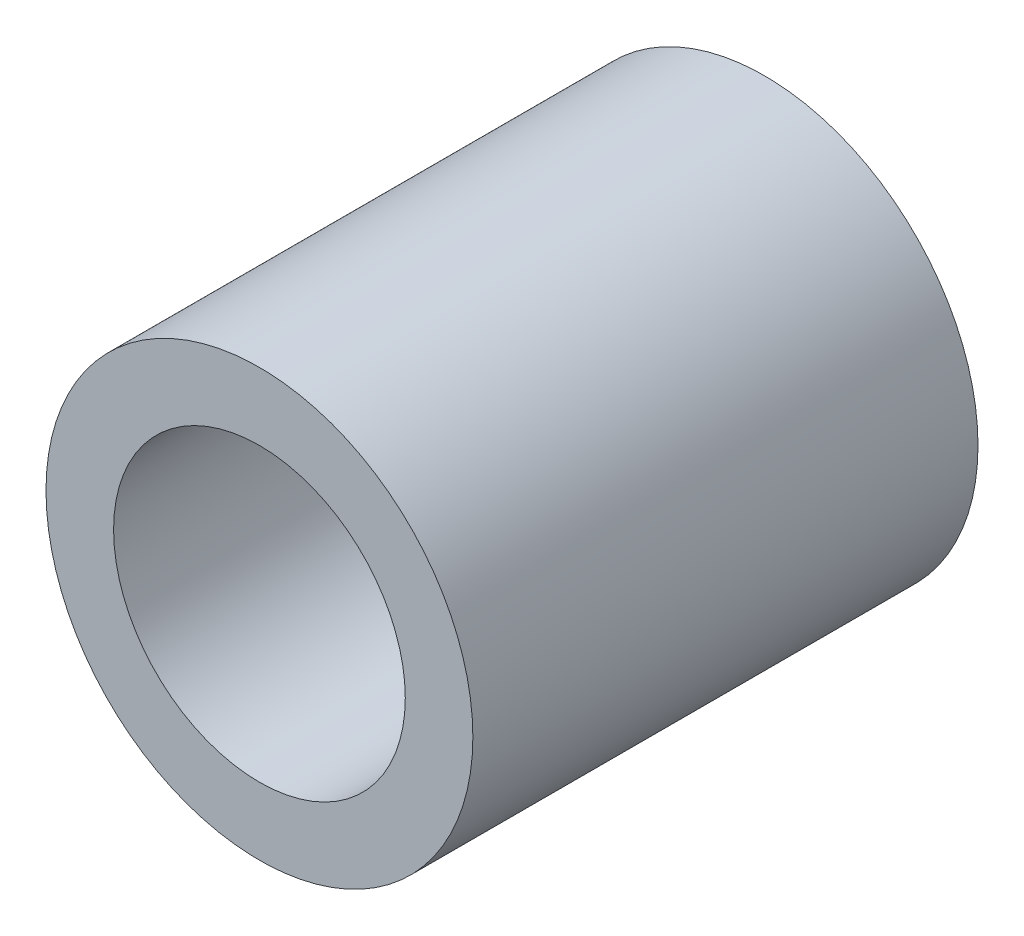
SolidWorks part; units mm, degrees
material "ABS PC"
ref_plane "Front Plane" through (0, 0, 0) normal (0, 0, 1) x (1, 0, 0)
ref_plane "Top Plane" through (0, 0, 0) normal (0, 1, 0) x (1, 0, 0)
ref_plane "Right Plane" through (0, 0, 0) normal (1, 0, 0) x (0, 0, -1)
sketch "Sketch1" plane through (0, 0, 0) normal (0, 0, 1) x (1, 0, 0)
  circle A0 centre (0, 0) radius 2.05
  circle A1 centre (0, 0) radius 3
  dimension "D1" = 4.1
  dimension "D2" = 6
extrude "Boss-Extrude1" add sketch "Sketch1" along normal blind 7.1
